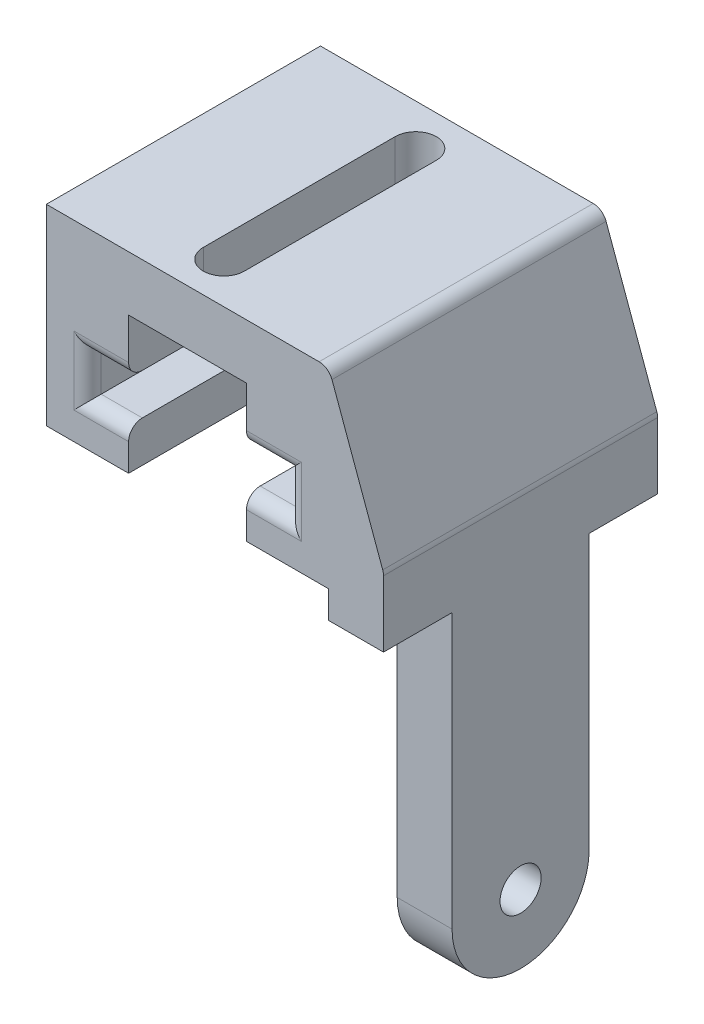
SolidWorks part; units mm, degrees
ref_plane "前视基准面" through (0, 0, 0) normal (0, 0, 1) x (1, 0, 0)
ref_plane "上视基准面" through (0, 0, 0) normal (0, 1, 0) x (1, 0, 0)
ref_plane "右视基准面" through (0, 0, 0) normal (1, 0, 0) x (0, 0, -1)
sketch "草图1" plane through (0, 0, 0) normal (0, 0, 1) x (1, 0, 0)
  line L16 (20.6, 14) -> (24.6, 3)
  line L30 (0, 0) -> (0, 14) construction
  line L31 (6, 6) -> (3, 6)
  line L32 (3, 6) -> (3, 3)
  line L33 (3, 3) -> (6, 3)
  line L34 (6, 3) -> (6, 0)
  line L35 (6, 0) -> (0, 0)
  line L36 (10.3, 17.7242) -> (10.3, -8.7509) construction
  line L37 (14.6, 0) -> (20.6, 0)
  line L38 (14.6, 3) -> (14.6, 0)
  line L39 (17.6, 3) -> (14.6, 3)
  line L40 (17.6, 6) -> (17.6, 3)
  line L41 (14.6, 6) -> (17.6, 6)
  line L42 (20.6, 0) -> (20.6, 14) construction
  line L43 (20.6, 14) -> (0, 14)
  line L44 (6, 6) -> (6, 10)
  line L45 (6, 10) -> (14.6, 10)
  line L46 (14.6, 10) -> (14.6, 6)
  line L51 (0, 14) -> (0, 0)
  line L52 (24.6, 3) -> (24.6, -2)
  line L53 (24.6, -2) -> (20.6, -2)
  line L54 (20.6, -2) -> (20.6, 0)
  point P44 (10.3, 9.8)
  point P45 (10.3, 9.8)
  dimension "D2" = 2
  dimension "D3" = 4
  dimension "D14" = 14
  dimension "D15" = 8
  dimension "D16" = 4
extrude "凸台-拉伸1" add sketch "草图1" along normal blind 20
sketch "草图2" plane through (24.6, 0, 0) normal (1, 0, 0) x (0, 0, -1)
  line L0 (-15, -2) -> (-5, -2)
  line L1 (-15, -2) -> (-15, -22)
  line L2 (-5, -2) -> (-5, -22)
  line L3 (-10, -2) -> (-10, -27.9019) construction
  line L4 (-20, 0) -> (0, 0) construction
  line L5 (-20, -2) -> (-20, 3) construction
  arc A0 (-15, -22) -> (-5, -22) centre (-10, -22) ccw
  circle A1 centre (-10, -22) radius 1.5
  dimension "D2" = 3
  dimension "D1" = 10
  dimension "D3" = 22
  dimension "D4" = 5
extrude "凸台-拉伸2" add sketch "草图2" against normal up to surface (4 mm away) up to face at (20.6, -1, 10)
fillet "圆角5" radius 1 14 edges at (4.5, 3, 0) (3, 4.5, 0) (4.5, 6, 0) (16.1, 6, 0) (17.6, 4.5, 0) (16.1, 3, 0) (16.1, 3, 20) (17.6, 4.5, 20) (16.1, 6, 20) (4.5, 6, 20) (3, 4.5, 20) (4.5, 3, 20) (20.6, 14, 10) (24.6, 3, 10)
sketch "草图3" plane through (0, 14, 0) normal (0, 1, 0) x (1, 0, 0)
  line L0 (9.9498, 1.388) -> (9.9498, -21.8584) construction
  line L1 (19.8996, 0) -> (0, 0) construction
  line L2 (19.8996, -20) -> (0, -20) construction
  line L3 (8.4498, -3) -> (8.4498, -17)
  line L4 (11.4498, -17) -> (11.4498, -3)
  arc A0 (11.4498, -3) -> (8.4498, -3) centre (9.9498, -3) ccw
  arc A1 (8.4498, -17) -> (11.4498, -17) centre (9.9498, -17) ccw
  dimension "D1" = 3
  dimension "D2" = 3
  dimension "D3" = 3
  dimension "D4" = 3
extrude "切除-拉伸1" cut sketch "草图3" against normal up to next
